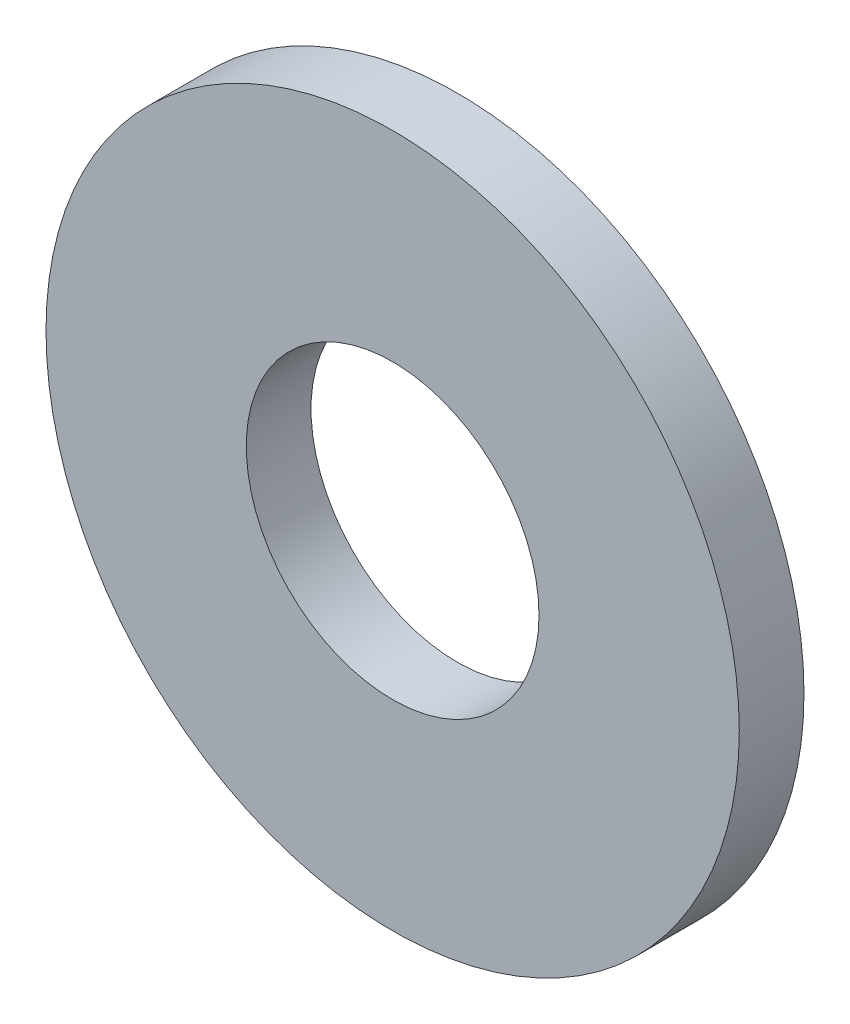
SolidWorks part; units mm, degrees
material "Alloy Steel"
ref_plane "Front Plane" through (0, 0, 0) normal (0, 0, 1) x (1, 0, 0)
ref_plane "Top Plane" through (0, 0, 0) normal (0, 1, 0) x (1, 0, 0)
ref_plane "Right Plane" through (0, 0, 0) normal (1, 0, 0) x (0, 0, -1)
sketch "Sketch1" plane through (0, 0, 0) normal (0, 0, 1) x (1, 0, 0)
  circle A0 centre (0, 0) radius 2.413
  circle A1 centre (0, 0) radius 5.715
  dimension "D1" = 4.826
  dimension "D2" = 11.43
extrude "Boss-Extrude1" add sketch "Sketch1" along normal blind 1.0668
